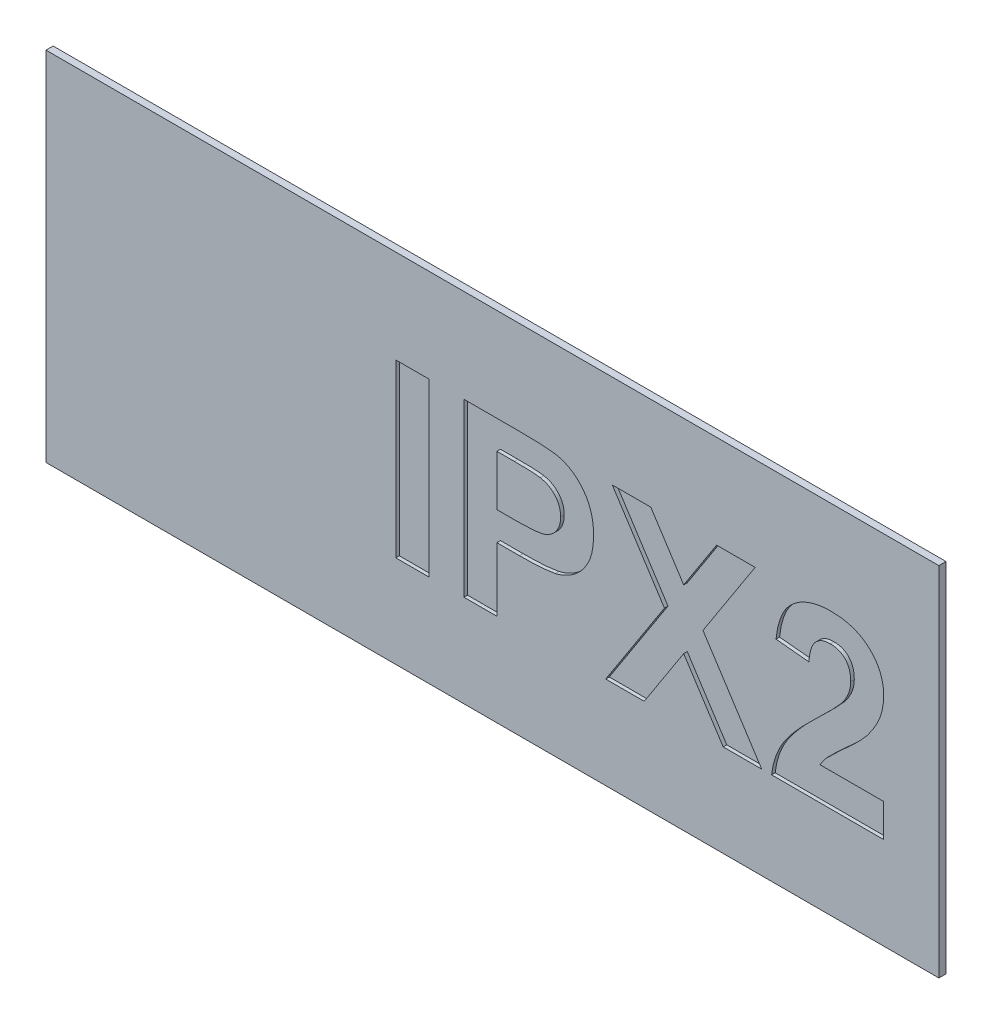
SolidWorks part; units mm, degrees
ref_plane "Front Plane" through (0, 0, 0) normal (0, 0, 1) x (1, 0, 0)
ref_plane "Top Plane" through (0, 0, 0) normal (0, 1, 0) x (1, 0, 0)
ref_plane "Right Plane" through (0, 0, 0) normal (1, 0, 0) x (0, 0, -1)
sketch "Sketch1" plane through (0, 0, 0) normal (0, 0, 1) x (1, 0, 0)
  line L1 (-12.5, -5) -> (12.5, -5)
  line L2 (-12.5, -5) -> (-12.5, 5)
  line L3 (-12.5, 5) -> (12.5, 5)
  line L4 (12.5, -5) -> (12.5, 5)
  line L5 (-12.5, -5) -> (12.5, 5) construction
  line L6 (-12.5, 5) -> (12.5, -5) construction
  point P0 (0, 0)
  dimension "D1" = 25
  dimension "D2" = 10
extrude "Boss-Extrude1" add sketch "Sketch1" along normal blind 0.2
sketch "Sketch2" plane through (0, 0, 0.2) normal (0, 0, 1) x (1, 0, 0)
  line L0 (-3.1367, -2.4152) -> (10.3851, -2.4152) construction
  text T0 "<b>IPX2</b>" font "Arial" height 4.8
extrude "Cut-Extrude1" cut sketch "Sketch2" against normal blind 0.1
